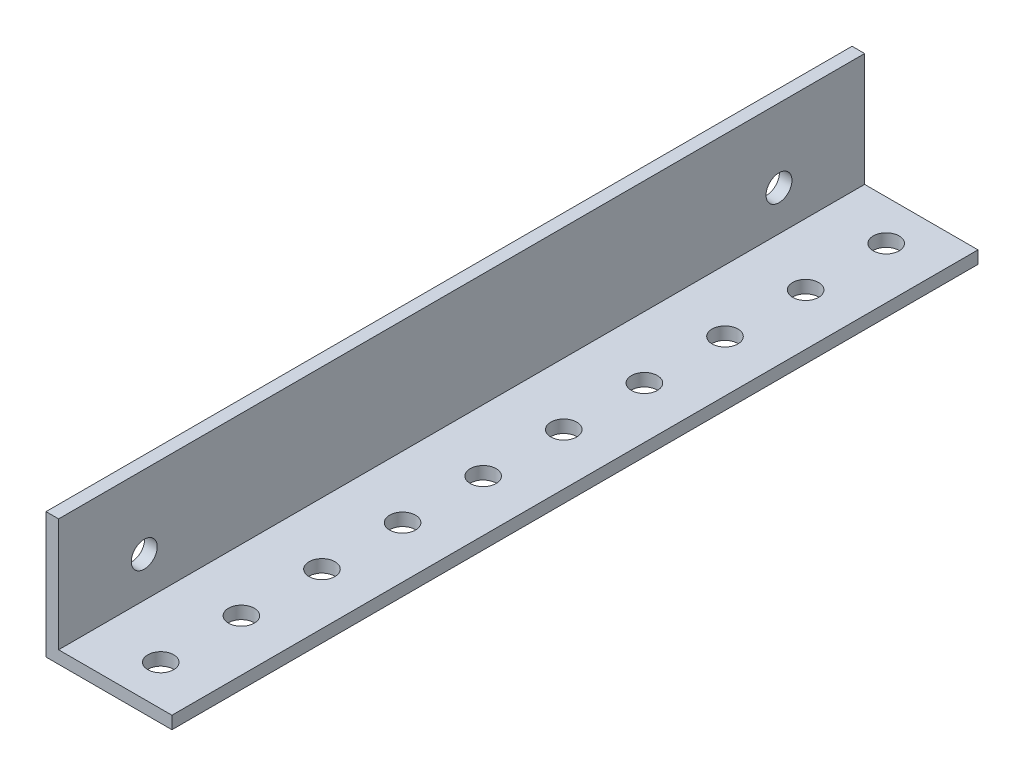
SolidWorks part; units mm, degrees
material "6061-T6 (SS)"
ref_plane "Front Plane" through (0, 0, 0) normal (0, 0, 1) x (1, 0, 0)
ref_plane "Top Plane" through (0, 0, 0) normal (0, 1, 0) x (1, 0, 0)
ref_plane "Right Plane" through (0, 0, 0) normal (1, 0, 0) x (0, 0, -1)
sketch "Sketch1" plane through (0, 0, 0) normal (0, 0, 1) x (1, 0, 0)
  line L0 (0, 0) -> (0, 15.875)
  line L1 (0, 15.875) -> (1.5875, 15.875)
  line L2 (1.5875, 15.875) -> (1.5875, 1.5875)
  line L3 (1.5875, 1.5875) -> (15.875, 1.5875)
  line L4 (15.875, 1.5875) -> (15.875, 0)
  line L5 (15.875, 0) -> (0, 0)
  dimension "D1" = 15.875
  dimension "D2" = 1.5875
  dimension "D3" = 15.875
extrude "Extrude1" add sketch "Sketch1" along normal mid plane 101.6
sketch "Sketch2" plane through (0, 1.5875, 0) normal (0, 1, 0) x (1, 0, 0)
  line L0 (15.875, 45.72) -> (9.3853, 45.72) construction
  line L1 (9.3853, 45.72) -> (1.5875, 45.72) construction
  line L3 (1.5875, -50.8) -> (1.5875, 50.8) construction
  line L4 (15.875, 50.8) -> (1.5875, 50.8) construction
  point P6 (7.1437, 0)
  dimension "D1" = 7.7978
  dimension "D2" = 5.08
hole_wizard "#4 Clearance Hole1" positions "3DSketch1" profile "Sketch3" hole size "#4" standard "Ansi Inch"
sketch3d "3DSketch1"
  point P4 (9.3853, 1.5875, -45.72)
sketch "Sketch3" plane through (9.3853, 1.5875, -45.72) normal (1, 0, 0) x (0, 0, 1)
  line L0 (0, 0) -> (0, 16.2206)
  line L1 (0, 16.2206) -> (1.6319, 15.24)
  line L2 (1.6319, 15.24) -> (1.6319, 0)
  line L5 (1.6319, 0) -> (0, 0)
  line L10 (0, 16.2206) -> (-1.6319, 15.24) construction
  line L11 (0, -6.35) -> (0, 107.95) construction
  dimension "Hole Dia." = 3.2639
  dimension "Hole Depth" = 15.24
  dimension "Drill Angle" = 118
pattern_linear "LPattern1" count 10 spacing 10.16 along (0, 0, 1) of "#4 Clearance Hole1"
sketch "Sketch4" plane through (1.5875, 0, 0) normal (1, 0, 0) x (0, 0, -1)
  line L0 (40.005, 1.5875) -> (40.005, 6.6218) construction
  line L1 (-40.005, 1.5875) -> (-40.005, 6.6218) construction
  line L2 (-50.8, 1.5875) -> (50.8, 1.5875) construction
  line L4 (40.005, 6.6218) -> (0, 6.6218) construction
  line L5 (0, 6.6218) -> (-40.005, 6.6218) construction
  line L6 (0, 1.5875) -> (0, 6.6218) construction
  point P6 (-63.5, 7.1437)
  dimension "D1" = 40.005
  dimension "D2" = 5.0343
hole_wizard "#4 Clearance Hole2" positions "3DSketch2" profile "Sketch5" hole size "#4" standard "Ansi Inch"
sketch3d "3DSketch2"
  point P9 (1.5875, 6.6218, -40.005)
  point P13 (1.5875, 6.6218, 40.005)
sketch "Sketch5" plane through (1.5875, 6.6218, -40.005) normal (0, 1, 0) x (0, 0, -1)
  line L0 (0, 0) -> (0, 16.2206)
  line L1 (0, 16.2206) -> (1.6319, 15.24)
  line L2 (1.6319, 15.24) -> (1.6319, 0)
  line L5 (1.6319, 0) -> (0, 0)
  line L10 (0, 16.2206) -> (-1.6319, 15.24) construction
  line L11 (0, -6.35) -> (0, 107.95) construction
  dimension "Hole Dia." = 3.2639
  dimension "Hole Depth" = 15.24
  dimension "Drill Angle" = 118
chamfer "Chamfer1" [suppressed] distance 10.16 angle 45
